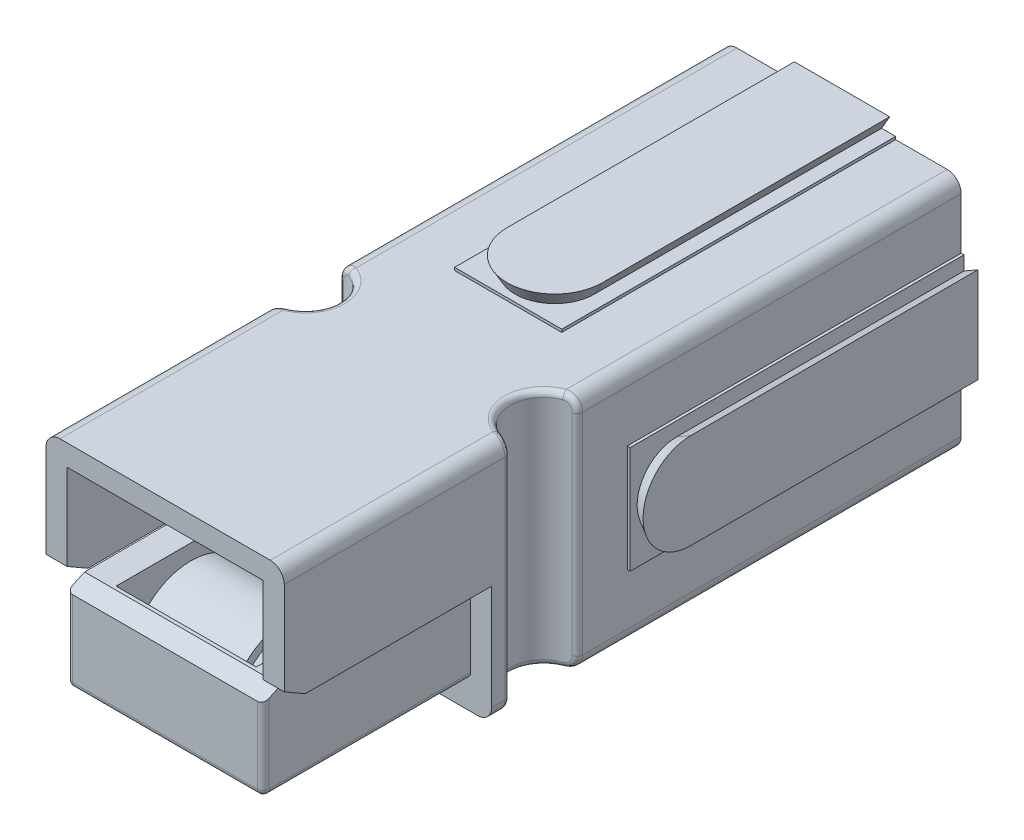
SolidWorks part; units mm, degrees
ref_plane "Face" through (0, 0, 0) normal (0, 0, 1) x (1, 0, 0)
ref_plane "Dessus" through (0, 0, 0) normal (0, 1, 0) x (1, 0, 0)
ref_plane "Droite" through (0, 0, 0) normal (1, 0, 0) x (0, 0, -1)
sketch "Esquisse1" plane through (0, 0, 0) normal (0, 0, 1) x (1, 0, 0)
  line L0 (0, 4.25) -> (0, -4.25) construction
  line L1 (-4.25, 4.25) -> (4.25, 4.25)
  line L2 (-4.25, 4.25) -> (-4.25, -4.25)
  line L3 (-4.25, -4.25) -> (4.25, -4.25)
  line L4 (4.25, 4.25) -> (4.25, -4.25)
  line L5 (-4.25, 0) -> (4.25, 0) construction
  line L9 (-1.4113, 4.25) -> (1.4113, 4.25) construction
  line L10 (-1.7, 4.75) -> (1.7, 4.75) construction
  line L11 (0, 4.75) -> (0, 4.25) construction
  line L12 (1.7, 4.75) -> (1.4113, 4.25) construction
  line L15 (-1.7, 4.75) -> (-1.4113, 4.25) construction
  line L16 (4.25, 1.4113) -> (4.25, -1.4113) construction
  line L17 (4.75, 0) -> (4.25, 0) construction
  line L18 (4.75, 1.7) -> (4.75, -1.7) construction
  line L19 (4.75, -1.7) -> (4.25, -1.4113) construction
  line L20 (4.75, 1.7) -> (4.25, 1.4113) construction
  point P4 (0, 4.25)
  point P6 (-4.25, 0)
  dimension "D1" = 8.5
  dimension "D2" = 8.5
extrude "Extrusion1" add sketch "Esquisse1" along normal blind 24.15
sketch "Esquisse5" plane through (0, 0, 24.15) normal (0, 0, 1) x (1, 0, 0)
  line L0 (0, 3.75) -> (0, -5.3524) construction
  line L4 (-4.25, 0) -> (-4.25, -4.25)
  line L7 (4.25, -4.25) -> (4.25, 0)
  line L8 (-4.25, -4.25) -> (4.25, -4.25) construction
  line L9 (-4.25, -4.25) -> (4.25, -4.25) construction
  line L11 (-4.25, 0) -> (-3.5, 0)
  line L12 (3.5, 0) -> (4.25, 0)
  line L13 (-4.25, -4.25) -> (4.25, -4.25)
  line L14 (4.25, -4.25) -> (4.25, 4.25) construction
  line L15 (-2.943, 0) -> (2.943, 0) construction
  line L16 (-3.5, 0) -> (-3.5, -3.25)
  line L17 (3.5, -3.25) -> (3.5, 0)
  line L18 (0, -3.25) -> (-3.5, -3.25)
  line L19 (0, -3.25) -> (3.5, -3.25)
  point P22 (0, -4.25)
  dimension "D1" = 0.75
  dimension "D2" = 1
  dimension "D3" = 5.886
  dimension "D4" = 7
  dimension "D5" = 0.75
  dimension "D6" = 8.5
  dimension "D7" = 4.25
extrude "Enlèv. mat.-Extru.5" cut sketch "Esquisse5" against normal blind 7.4
ref_plane "Plane2" through (0, 0, 16.75) normal (0, 0, 1) x (1, 0, 0)
sketch "Sketch2" plane through (0, 0, 16.75) normal (0, 0, 1) x (1, 0, 0)
  line L0 (-3.5, -0.05) -> (3.5, -0.05)
  line L1 (0, 4.25) -> (0, -4.25) construction
  line L2 (-3.5, 3.5) -> (-3.5, -0.05)
  line L4 (-4.25, 0) -> (4.25, 0) construction
  line L5 (3.5, 3.5) -> (3.5, -0.05)
  line L6 (-3.5, 3.5) -> (3.5, 3.5)
extrude "Cut-Extrude12" cut sketch "Sketch2" along normal blind 8
sketch "Esquisse8" plane through (0, 0, 0) normal (0, 0, -1) x (-1, 0, 0)
  line L0 (-4.25, -4.25) -> (-4.25, 4.25) construction
  line L1 (-4.25, 4.25) -> (4.25, 4.25) construction
  line L37 (2.85, 4.25) -> (2.85, -4.25)
  line L38 (2.85, 2.85) -> (2.85, -2.85)
  line L41 (-2.85, 2.85) -> (-2.85, -2.85)
  line L43 (4.25, -2.85) -> (-4.25, -2.85)
  line L44 (2.85, -2.85) -> (-2.85, -2.85)
  line L47 (2.85, 2.85) -> (-2.85, 2.85)
  dimension "D2" = 1.4
  dimension "D4" = 1.4
  dimension "D1" = 1.4
  dimension "D3" = 1.4
extrude "Enlèv. mat.-Extru.7" cut sketch "Esquisse8" against normal blind 10
sketch "Esquisse12" plane through (0, 0, 0) normal (0, 0, -1) x (-1, 0, 0)
  line L0 (0, 4.25) -> (0, -4.25) construction
  line L1 (-4.25, 4.25) -> (4.25, 4.25) construction
  line L2 (-4.25, 0) -> (4.25, 0) construction
  line L3 (3.75, 1.7) -> (4.25, 1.4113)
  line L4 (-4.25, -4.25) -> (-4.25, 4.25) construction
  line L6 (3.75, -1.7) -> (3.75, 1.7)
  line L7 (4.25, -1.4113) -> (3.75, -1.7)
  line L8 (4.25, 1.4113) -> (4.25, -1.4113)
  line L10 (-1.4113, -4.25) -> (1.4113, -4.25)
  line L13 (-1.4113, -4.25) -> (-1.7, -3.75)
  line L14 (1.7, -3.75) -> (1.4113, -4.25)
  line L15 (-1.7, -3.75) -> (1.7, -3.75)
  dimension "D1" = 4.25
  dimension "D2" = 4.25
  dimension "D3" = 3.4
extrude "Cut-Extrude7" cut sketch "Esquisse12" against normal blind 10.25
ref_plane "Plane3" through (0, 0, 10.25) normal (0, 0, -1) x (-1, 0, 0)
sketch "Sketch3" plane through (0, 0, 10.25) normal (0, 0, -1) x (-1, 0, 0)
  line L0 (3.75, 0) -> (4.25, 0) construction
  line L1 (3.75, 1.7) -> (3.75, -1.7) construction
  line L2 (4.25, -1.4113) -> (4.25, 1.4113) construction
  line L3 (3.75, 0) -> (3.75, -1.7)
  line L4 (3.75, -1.7) -> (4.25, -1.4113)
  line L5 (4.25, -1.4113) -> (4.25, 0)
  line L6 (3.75, 0) -> (4.25, 0)
revolve "Cut-Revolve1" cut sketch "Sketch3" angle 180 about L0
ref_plane "Plane14" through (-4.25, 0, 0) normal (-1, 0, 0) x (0, 0, 1)
sketch "Sketch14" plane through (-4.25, 0, 0) normal (-1, 0, 0) x (0, 0, 1)
  line L0 (0, 0) -> (11.6613, 0) construction
  line L1 (0, 1.4113) -> (10.25, 1.4113)
  line L2 (10.25, 1.4113) -> (10.25, -1.4113) construction
  line L3 (0, -1.4113) -> (10.25, -1.4113)
  line L5 (0, 1.4113) -> (0, 1.9113)
  line L6 (0, 4.25) -> (0, 1.4113) construction
  line L7 (0, 1.9113) -> (11.9113, 1.9113)
  line L8 (0, -1.4113) -> (0, -1.9113)
  line L9 (0, -1.4113) -> (0, -4.25) construction
  line L10 (0, -1.9113) -> (11.9113, -1.9113)
  line L13 (11.9113, 1.9113) -> (11.9113, -1.9113)
  arc A0 (10.25, -1.4113) -> (10.25, 1.4113) centre (10.25, 0) ccw construction
  arc A1 (10.25, 1.4113) -> (10.25, -1.4113) centre (10.25, 0) cw
extrude "Boss-Extrude5" add sketch "Sketch14" along normal blind 0.1
ref_plane "Plane4" through (0, 0, 10.25) normal (0, 0, -1) x (-1, 0, 0)
sketch "Sketch4" plane through (0, 0, 10.25) normal (0, 0, -1) x (-1, 0, 0)
  line L0 (0, -3.75) -> (0, -4.25) construction
  line L1 (1.7, -3.75) -> (-1.7, -3.75) construction
  line L2 (-1.4113, -4.25) -> (1.4113, -4.25) construction
  line L3 (0, -3.75) -> (1.7, -3.75)
  line L4 (1.7, -3.75) -> (1.4113, -4.25)
  line L5 (1.4113, -4.25) -> (0, -4.25)
  line L6 (0, -3.75) -> (0, -4.25)
revolve "Cut-Revolve2" cut sketch "Sketch4" angle 180 about L0
ref_plane "Plane15" through (0, -4.25, 0) normal (0, -1, 0) x (1, 0, 0)
sketch "Sketch15" plane through (0, -4.25, 0) normal (0, -1, 0) x (1, 0, 0)
  line L4 (-1.4113, 0) -> (-1.4113, 10.25)
  line L6 (-1.9113, 0) -> (-1.9113, 11.9113)
  line L9 (-1.9113, 11.9113) -> (1.9113, 11.9113)
  line L11 (-1.4113, 0) -> (-1.9113, 0)
  line L12 (1.9113, 0) -> (1.9113, 11.9113)
  line L14 (0, 0) -> (0, 11.6613) construction
  line L15 (1.4113, 0) -> (1.4113, 10.25)
  line L16 (-1.4113, 10.25) -> (1.4113, 10.25) construction
  line L17 (1.4113, 0) -> (1.9113, 0)
  arc A0 (-1.4113, 10.25) -> (1.4113, 10.25) centre (0, 10.25) cw
extrude "Boss-Extrude6" add sketch "Sketch15" along normal blind 0.1
ref_plane "Plane16" through (0, 4.25, 0) normal (0, 1, 0) x (-1, 0, 0)
sketch "Sketch16" plane through (0, 4.25, 0) normal (0, 1, 0) x (-1, 0, 0)
  line L0 (-1.9113, 0) -> (1.9113, 0)
  line L6 (0, 0) -> (0, 11.6613) construction
  line L12 (-1.9113, 0) -> (-1.9113, 11.9113)
  line L15 (-1.9113, 11.9113) -> (1.9113, 11.9113)
  line L16 (1.9113, 0) -> (1.9113, 11.9113)
extrude "Boss-Extrude7" add sketch "Sketch16" along normal blind 0.1
ref_plane "Plane17" through (4.25, 0, 0) normal (1, 0, 0) x (0, 0, -1)
sketch "Sketch17" plane through (4.25, 0, 0) normal (1, 0, 0) x (0, 0, -1)
  line L0 (0, 1.9113) -> (0, -1.9113)
  line L11 (0, 1.9113) -> (-11.9113, 1.9113)
  line L12 (-11.9113, -1.9113) -> (-11.9113, 1.9113)
  line L15 (0, -1.9113) -> (-11.9113, -1.9113)
  line L16 (0, 0) -> (-11.6613, 0) construction
extrude "Boss-Extrude8" add sketch "Sketch17" along normal blind 0.1
ref_plane "Plane5" through (0, 0, 0) normal (0, 0, -1) x (-1, 0, 0)
sketch "Sketch5" plane through (0, 0, 0) normal (0, 0, -1) x (-1, 0, 0)
  line L0 (0, 4.25) -> (0, -4.25) construction
  line L1 (1.4113, 4.35) -> (-1.4113, 4.35)
  line L3 (-1.4113, 4.35) -> (-1.7, 4.85)
  line L4 (-1.7, 4.85) -> (1.7, 4.85)
  line L5 (-1.4113, -4.25) -> (1.4113, -4.25) construction
  line L6 (1.7, 4.85) -> (1.4113, 4.35)
  line L9 (-4.25, 0) -> (4.25, 0) construction
  line L10 (-4.85, -1.7) -> (-4.85, 1.7)
  line L11 (-4.85, 1.7) -> (-4.35, 1.4113)
  line L12 (-4.35, 1.4113) -> (-4.35, -1.4113)
  line L13 (-4.35, -1.4113) -> (-4.85, -1.7)
extrude "Boss-Extrude4" add sketch "Sketch5" against normal blind 10.25
ref_plane "Plane6" through (0, 0, 10.25) normal (0, 0, 1) x (1, 0, 0)
sketch "Sketch6" plane through (0, 0, 10.25) normal (0, 0, 1) x (1, 0, 0)
  line L0 (0, 4.85) -> (0, 4.25) construction
  line L1 (-1.7, 4.85) -> (1.7, 4.85) construction
  line L2 (4.25, 4.25) -> (-4.25, 4.25) construction
  line L3 (0, 4.35) -> (1.4113, 4.35)
  line L5 (1.7, 4.85) -> (0, 4.85)
  line L6 (0, 4.85) -> (0, 4.35)
  line L8 (-1.9113, 4.35) -> (1.9113, 4.35) construction
  line L9 (1.4113, 4.35) -> (1.7, 4.85)
revolve "Revolve1" add sketch "Sketch6" angle 180 about L0
ref_plane "Plane7" through (0, 0, 10.25) normal (0, 0, 1) x (1, 0, 0)
sketch "Sketch7" plane through (0, 0, 10.25) normal (0, 0, 1) x (1, 0, 0)
  line L0 (4.85, 0) -> (4.25, 0) construction
  line L1 (4.85, 1.7) -> (4.85, -1.7) construction
  line L4 (4.85, -1.7) -> (4.85, 0)
  line L5 (4.85, 0) -> (4.35, 0)
  line L6 (4.35, 0) -> (4.35, -1.4113)
  line L7 (4.35, -1.4113) -> (4.35, 1.4113) construction
  line L8 (4.35, -1.4113) -> (4.85, -1.7)
revolve "Revolve2" add sketch "Sketch7" angle 180 about L0
ref_plane "Plane13" through (0, -0.05, 0) normal (0, 1, 0) x (-1, 0, 0)
sketch "Sketch13" plane through (0, -0.05, 0) normal (0, 1, 0) x (-1, 0, 0)
  line L0 (0, 24.15) -> (0, 16.75) construction
  line L4 (-2.5, 16.75) -> (2.5, 16.75)
  line L7 (-2.5, 23.4) -> (-2.5, 16.75)
  line L8 (2.5, 16.75) -> (2.5, 23.4)
  line L9 (2.5, 23.4) -> (-2.5, 23.4)
extrude "Cut-Extrude16" cut sketch "Sketch13" against normal blind 2.5
ref_plane "Plan1" through (0, 0, 0) normal (1, 0, 0) x (0, 0, -1)
sketch "Esquisse13" plane through (0, 0, 0) normal (1, 0, 0) x (0, 0, -1)
  line L0 (-20.0219, -0.4036) -> (-16.75, -1.3209)
  line L2 (-20.1718, -0.6731) -> (-16.75, -1.6325)
  line L3 (-23.3055, -1.5523) -> (-23.5952, -1.4741)
  line L4 (-16.75, -1.6325) -> (-16.75, -1.3209)
  line L5 (-20.1718, -0.6731) -> (-16.831, -1.6098) construction
  arc A0 (-23.5952, -1.4741) -> (-20.0219, -0.4036) centre (-21.477, -2.0455) cw
  arc A1 (-23.3055, -1.5523) -> (-20.1718, -0.6731) centre (-21.477, -2.0455) cw
  dimension "D1" = 0.3
extrude "Extrusion2" add sketch "Esquisse13" along normal blind 1.75 and the other way blind 1.75
ref_plane "Plane9" through (0, 0, 10) normal (0, 0, -1) x (-1, 0, 0)
sketch "Sketch9" plane through (0, 0, 10) normal (0, 0, -1) x (-1, 0, 0)
  line L0 (0, 2.85) -> (0, -2.85) construction
  line L3 (-2.85, 0) -> (2.85, 0) construction
  circle A0 centre (0, 0) radius 2.85 construction
  circle A1 centre (0, 0) radius 2
extrude "Cut-Extrude9" cut sketch "Sketch9" against normal blind 6.75
ref_plane "Plane10" through (0, 4.25, 0) normal (0, 1, 0) x (-1, 0, 0)
sketch "Sketch10" plane through (0, 4.25, 0) normal (0, 1, 0) x (-1, 0, 0)
  line L0 (0, 24.15) -> (0, 14.893) construction
  line L1 (-4.25, 24.15) -> (4.25, 24.15) construction
  line L2 (0, 16.75) -> (0, 10) construction
  line L3 (-4.25, 14.893) -> (4.25, 14.893) construction
  line L4 (4.25, 13.693) -> (4.25, 16.093)
  line L5 (-4.25, 13.693) -> (-4.25, 16.093)
  arc A0 (4.25, 16.093) -> (4.25, 13.693) centre (4.25, 14.893) ccw
  arc A1 (-4.25, 16.093) -> (-4.25, 13.693) centre (-4.25, 14.893) cw
  dimension "D2" = 2.4
  dimension "D1" = 9.257
extrude "Cut-Extrude10" cut sketch "Sketch10" against normal blind 8.6
fillet "Fillet1" radius 0.5 8 edges at (-4.25, -4.25, 16.4215) (-4.25, -4.25, 6.8465) (4.25, -4.25, 6.8465) (4.25, -4.25, 16.4215) (-4.25, 4.25, 20.1215) (-4.25, 4.25, 6.8465) (4.25, 4.25, 20.1215) (4.25, 4.25, 6.8465)
fillet "Fillet2" radius 0.2 21 edges at (-4.1408, -4.0619, 13.698) (-3.05, -4.25, 14.893) (-4.0497, -4.1503, 16.0762) (-4.25, 0, 16.093) (-4.1408, 4.0619, 16.088) (-3.05, 4.25, 14.893) (-4.0497, 4.1503, 13.7098) (4.1408, 4.0619, 13.698) (4.25, 0, 13.693) (4.0497, -4.1503, 13.7098) (3.05, -4.25, 14.893) (4.1408, -4.0619, 16.088) (4.25, 0, 16.093) (4.0497, 4.1503, 16.0762) (-4.25, 0, 13.693) (3.05, 4.25, 14.893) (-3.5, -3.25, 20.45) (-3.5, -1.65, 24.15) (0, -3.25, 24.15) (3.5, -1.65, 24.15) (3.5, -3.25, 20.45)
ref_plane "Plane11" through (0, 0, 0) normal (1, 0, 0) x (0, 0, -1)
sketch "Sketch11" plane through (0, 0, 0) normal (1, 0, 0) x (0, 0, -1)
  line L0 (-24.15, 0.433) -> (-24.15, 0)
  line L1 (-23.4, 0) -> (-24.15, 0)
  line L3 (-23.4, 0) -> (-24.15, 0.433)
  line L4 (-24.15, -0.05) -> (-24.15, -0.3387)
  line L6 (-24.15, -0.05) -> (-23.525, -0.05)
  line L9 (-23.525, -0.05) -> (-24.15, -0.3387)
  dimension "D1" = 0.75
  dimension "D2" = 30
extrude "Cut-Extrude11" cut sketch "Sketch11" against normal blind 4.5 and the other way blind 4.5
scale "Scale3" bodies to scale 137 scale about centroid uniform scaling yes scale factor 0.88624
